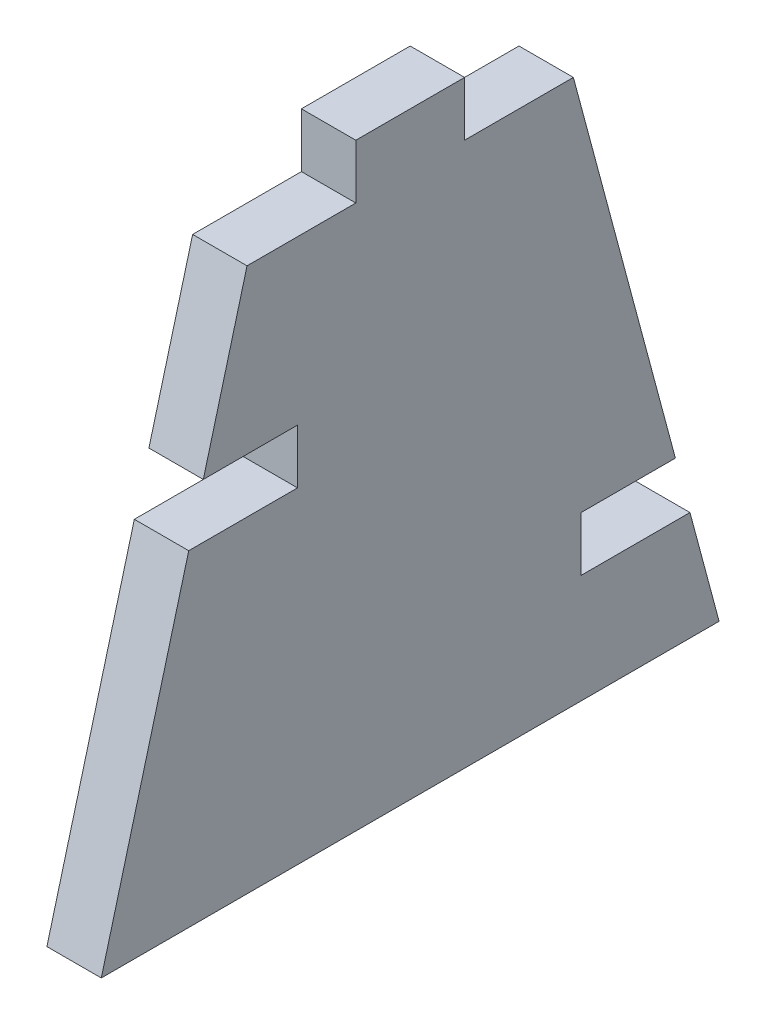
SolidWorks part; units mm, degrees
ref_plane "Front Plane" through (0, 0, 0) normal (0, 0, 1) x (1, 0, 0)
ref_plane "Top Plane" through (0, 0, 0) normal (0, 1, 0) x (1, 0, 0)
ref_plane "Right Plane" through (0, 0, 0) normal (1, 0, 0) x (0, 0, -1)
sketch "Sketch1" plane through (0, 0, 0) normal (1, 0, 0) x (0, 0, -1)
  line L0 (56.7949, 0) -> (-56.7949, 0)
  line L1 (-56.7949, 0) -> (-40.718, 60)
  line L2 (-30, 100) -> (-10, 100)
  line L3 (-10, 100) -> (-10, 110)
  line L4 (-10, 110) -> (10, 110)
  line L5 (0, 110) -> (0, 0) construction
  line L6 (-38.0385, 70) -> (-20.718, 70)
  line L7 (-20.718, 70) -> (-20.718, 60)
  line L8 (-20.718, 60) -> (-40.718, 60)
  line L9 (-38.0385, 70) -> (-30, 100)
  line L10 (48.7564, 30) -> (40.718, 60)
  line L11 (10, 100) -> (10, 110)
  line L12 (56.7949, 0) -> (51.4359, 20)
  line L13 (38.0385, 70) -> (40.718, 60)
  line L14 (38.0385, 70) -> (30, 100)
  line L15 (30, 100) -> (10, 100)
  line L16 (48.7564, 30) -> (31.4359, 30)
  line L17 (31.4359, 30) -> (31.4359, 20)
  line L18 (31.4359, 20) -> (51.4359, 20)
  point P19 (41.4359, 20)
  dimension "D1" = 75
  dimension "D2" = 10
  dimension "D3" = 20
  dimension "D4" = 60
  dimension "D5" = 10
  dimension "D6" = 20
  dimension "D7" = 10
  dimension "D8" = 20
  dimension "D9" = 20
  dimension "D10" = 110
  dimension "D11" = 10
extrude "Boss-Extrude1" add sketch "Sketch1" along normal blind 10 contours L8 L1 L0 L12 L18 L17 L16 L10 L13 L14 L15 L11 L4 L3 L2 L9 L6 L7
